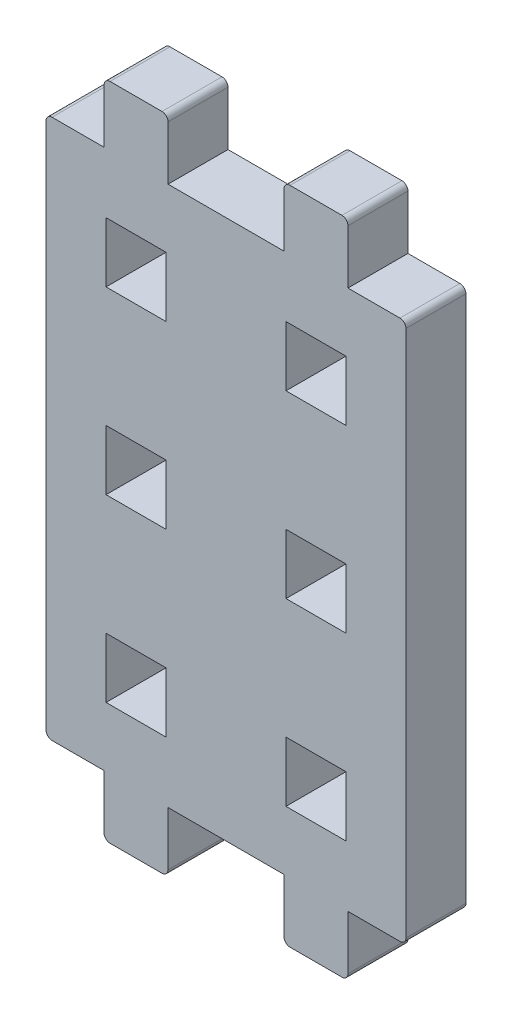
SolidWorks part; units mm, degrees
ref_plane "Alzado" through (0, 0, 0) normal (0, 0, 1) x (1, 0, 0)
ref_plane "Planta" through (0, 0, 0) normal (0, 1, 0) x (1, 0, 0)
ref_plane "Vista lateral" through (0, 0, 0) normal (1, 0, 0) x (0, 0, -1)
sketch "Model" plane through (0, 0, 0) normal (0, 0, 1) x (1, 0, 0)
  line L0 (12.2169, 292.9367) -> (12.2169, 289.9367)
  line L1 (15.2169, 292.9367) -> (12.2169, 292.9367)
  line L2 (15.2169, 289.9367) -> (15.2169, 292.9367)
  line L3 (12.2169, 289.9367) -> (15.2169, 289.9367)
  line L4 (21.2169, 292.9367) -> (21.2169, 289.9367)
  line L5 (24.2169, 292.9367) -> (21.2169, 292.9367)
  line L6 (24.2169, 289.9367) -> (24.2169, 292.9367)
  line L7 (21.2169, 289.9367) -> (24.2169, 289.9367)
  line L8 (12.2169, 274.9367) -> (12.2169, 271.9367)
  line L9 (15.2169, 274.9367) -> (12.2169, 274.9367)
  line L10 (15.2169, 271.9367) -> (15.2169, 274.9367)
  line L11 (12.2169, 271.9367) -> (15.2169, 271.9367)
  line L12 (21.2169, 274.9367) -> (21.2169, 271.9367)
  line L13 (24.2169, 274.9367) -> (21.2169, 274.9367)
  line L14 (24.2169, 271.9367) -> (24.2169, 274.9367)
  line L15 (21.2169, 271.9367) -> (24.2169, 271.9367)
  line L16 (12.2169, 283.9367) -> (12.2169, 280.9367)
  line L17 (15.2169, 283.9367) -> (12.2169, 283.9367)
  line L18 (15.2169, 280.9367) -> (15.2169, 283.9367)
  line L19 (12.2169, 280.9367) -> (15.2169, 280.9367)
  line L20 (21.2169, 283.9367) -> (21.2169, 280.9367)
  line L21 (24.2169, 283.9367) -> (21.2169, 283.9367)
  line L22 (24.2169, 280.9367) -> (24.2169, 283.9367)
  line L23 (21.2169, 280.9367) -> (24.2169, 280.9367)
  line L24 (9.2169, 295.6367) -> (9.2169, 269.2367)
  line L25 (27.2169, 295.6367) -> (27.2169, 269.2367)
  line L26 (12.1169, 298.6367) -> (12.1169, 295.9367)
  line L27 (15.3169, 295.9367) -> (15.3169, 298.6367)
  line L28 (12.4169, 298.9367) -> (15.0169, 298.9367)
  line L29 (9.5169, 295.9367) -> (12.1169, 295.9367)
  line L30 (15.3169, 295.9367) -> (21.1169, 295.9367)
  line L31 (21.1169, 298.6367) -> (21.1169, 295.9367)
  line L32 (24.3169, 295.9367) -> (24.3169, 298.6367)
  line L33 (21.4169, 298.9367) -> (24.0169, 298.9367)
  line L34 (24.3169, 295.9367) -> (26.9169, 295.9367)
  line L35 (12.1169, 266.2367) -> (12.1169, 268.9367)
  line L36 (15.3169, 268.9367) -> (15.3169, 266.2367)
  line L37 (12.4169, 265.9367) -> (15.0169, 265.9367)
  line L38 (9.5169, 268.9367) -> (12.1169, 268.9367)
  line L39 (15.3169, 268.9367) -> (21.1169, 268.9367)
  line L40 (21.1169, 266.2367) -> (21.1169, 268.9367)
  line L41 (24.3169, 268.9367) -> (24.3169, 266.2367)
  line L42 (21.4169, 265.9367) -> (24.0169, 265.9367)
  line L43 (24.3169, 268.9367) -> (26.9169, 268.9367)
  arc A0 (12.4169, 298.9367) -> (12.1169, 298.6367) centre (12.4169, 298.6367) ccw
  arc A1 (15.3169, 298.6367) -> (15.0169, 298.9367) centre (15.0169, 298.6367) ccw
  arc A2 (9.5169, 295.9367) -> (9.2169, 295.6367) centre (9.5169, 295.6367) ccw
  arc A3 (27.2169, 295.6367) -> (26.9169, 295.9367) centre (26.9169, 295.6367) ccw
  arc A4 (21.4169, 298.9367) -> (21.1169, 298.6367) centre (21.4169, 298.6367) ccw
  arc A5 (24.3169, 298.6367) -> (24.0169, 298.9367) centre (24.0169, 298.6367) ccw
  arc A6 (12.1169, 266.2367) -> (12.4169, 265.9367) centre (12.4169, 266.2367) ccw
  arc A7 (15.0169, 265.9367) -> (15.3169, 266.2367) centre (15.0169, 266.2367) ccw
  arc A8 (9.2169, 269.2367) -> (9.5169, 268.9367) centre (9.5169, 269.2367) ccw
  arc A9 (26.9169, 268.9367) -> (27.2169, 269.2367) centre (26.9169, 269.2367) ccw
  arc A10 (21.1169, 266.2367) -> (21.4169, 265.9367) centre (21.4169, 266.2367) ccw
  arc A11 (24.0169, 265.9367) -> (24.3169, 266.2367) centre (24.0169, 266.2367) ccw
extrude "Saliente-Extruir1" add sketch "Model" along normal blind 3
